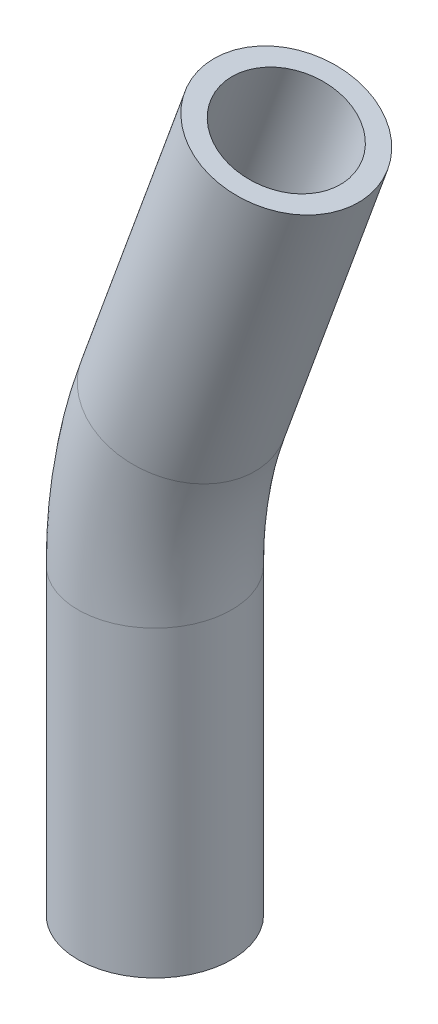
SolidWorks part; units mm, degrees
ref_plane "Front Plane" through (0, 0, 0) normal (0, 0, 1) x (1, 0, 0)
ref_plane "Top Plane" through (0, 0, 0) normal (0, 1, 0) x (1, 0, 0)
ref_plane "Right Plane" through (0, 0, 0) normal (1, 0, 0) x (0, 0, -1)
sketch "Sketch1" plane through (0, 0, 0) normal (0, 0, 1) x (1, 0, 0)
  line L0 (0, 0) -> (0, 15.7682)
  line L1 (1.4474, 23.9766) -> (6.8404, 38.7939)
  arc A0 (0, 15.7682) -> (1.4474, 23.9766) centre (24, 15.7682) cw
  point P6 (0, 20)
  dimension "D3" = 24
  dimension "D1" = 20
  dimension "D2" = 20
  dimension "D4" = 160
sketch "Sketch2" plane through (0, 0, 0) normal (0, 1, 0) x (1, 0, 0)
  circle A0 centre (0, 0) radius 4
  circle A1 centre (0, 0) radius 3
  dimension "D1" = 6
  dimension "D2" = 8
sweep "Sweep1" add profiles "Sketch2" path "Sketch1"
